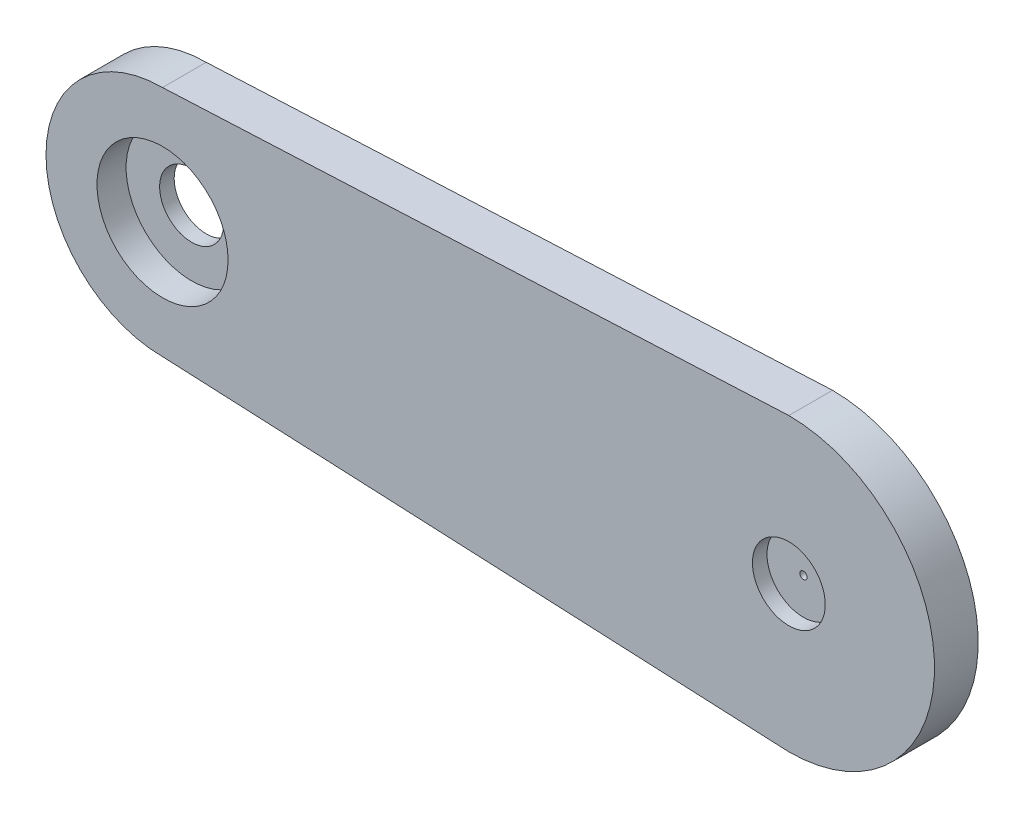
SolidWorks part; units mm, degrees
ref_plane "Alzado" through (0, 0, 0) normal (0, 0, 1) x (1, 0, 0)
ref_plane "Planta" through (0, 0, 0) normal (0, 1, 0) x (1, 0, 0)
ref_plane "Vista lateral" through (0, 0, 0) normal (1, 0, 0) x (0, 0, -1)
sketch "Croquis1" plane through (0, 0, 0) normal (0, 0, 1) x (1, 0, 0)
  line L0 (0, 0) -> (215, 0) construction
  line L1 (0, 40) -> (215, 50)
  line L2 (0, -40) -> (215, -50)
  circle A0 centre (0, 0) radius 1.25
  circle A1 centre (0, 0) radius 40
  circle A2 centre (215, 0) radius 50
  circle A3 centre (215, 0) radius 1.25
  dimension "D1" = 2.5
  dimension "D2" = 80
  dimension "D4" = 100
  dimension "D5" = 2.5
  dimension "D3" = 215
extrude "Saliente-Extruir1" add sketch "Croquis1" along normal blind 15
sketch "Croquis4" plane through (0, 0, 15) normal (0, 0, 1) x (1, 0, 0)
  circle A0 centre (0, 0) radius 22.5
  dimension "D1" = 45
sketch "Croquis5" plane through (0, 0, 0) normal (0, 0, -1) x (-1, 0, 0)
  circle A0 centre (0, 0) radius 11
  dimension "D1" = 22
extrude "Cortar-Extruir1" cut sketch "Croquis5" against normal blind 5
sketch "Croquis6" plane through (0, 0, 15) normal (0, 0, 1) x (1, 0, 0)
  circle A0 centre (215, 0) radius 12.5
  point P0 (215, 0)
  dimension "D3" = 25
extrude "Cortar-Extruir2" cut sketch "Croquis6" against normal blind 5
extrude "Cortar-Extruir3" cut sketch "Croquis4" against normal blind 10
